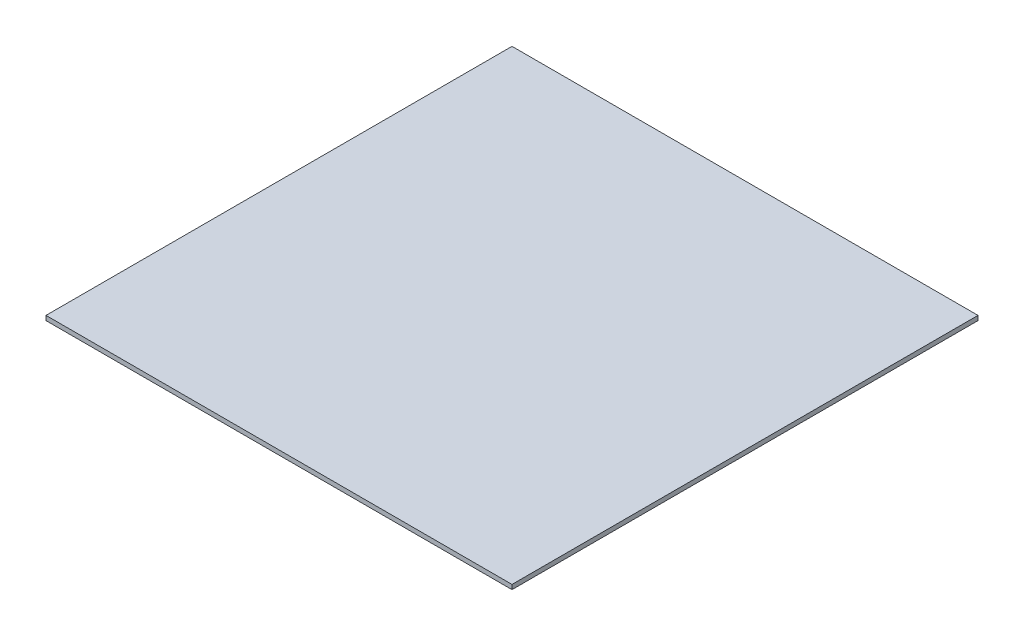
SolidWorks part; units mm, degrees
ref_plane "Front Plane" through (0, 0, 0) normal (0, 0, 1) x (1, 0, 0)
ref_plane "Top Plane" through (0, 0, 0) normal (0, 1, 0) x (1, 0, 0)
ref_plane "Right Plane" through (0, 0, 0) normal (1, 0, 0) x (0, 0, -1)
sketch "Sketch1" plane through (0, 0, 0) normal (0, 1, 0) x (1, 0, 0)
  line L1 (-205, 205) -> (205, 205)
  line L2 (-205, 205) -> (-205, -205)
  line L3 (-205, -205) -> (205, -205)
  line L4 (205, 205) -> (205, -205)
  line L5 (-205, 205) -> (205, -205) construction
  line L6 (-205, -205) -> (205, 205) construction
  point P0 (0, 0)
  dimension "D1" = 410
  dimension "D2" = 410
extrude "Boss-Extrude1" add sketch "Sketch1" along normal blind 4
